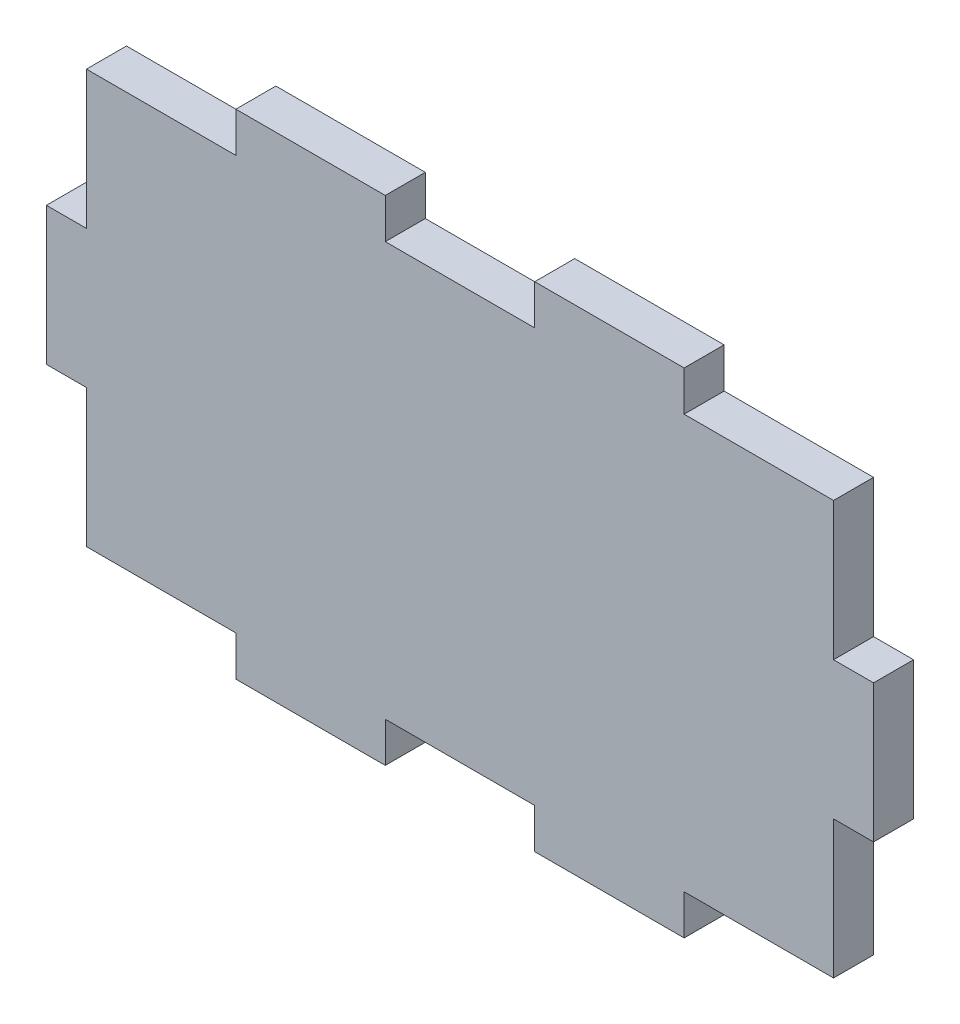
SolidWorks part; units mm, degrees
ref_plane "Plan de face" through (0, 0, 0) normal (0, 0, 1) x (1, 0, 0)
ref_plane "Plan de dessus" through (0, 0, 0) normal (0, 1, 0) x (1, 0, 0)
ref_plane "Plan de droite" through (0, 0, 0) normal (1, 0, 0) x (0, 0, -1)
sketch "Esquisse3" plane through (0, 0, 0) normal (0, 0, 1) x (1, 0, 0)
  line L0 (22.4, 0) -> (33.6, 0)
  line L1 (0, 0) -> (11.2, 0)
  line L2 (0, 0) -> (0, 10.33)
  line L3 (0, 31) -> (11.2, 31)
  line L4 (56, 0) -> (56, 10.33)
  line L6 (11.2, 31) -> (11.2, 34)
  line L8 (11.2, 34) -> (22.4, 34)
  line L9 (11.2, 0) -> (11.2, -3)
  line L10 (11.2, -3) -> (22.4, -3)
  line L11 (22.4, 0) -> (22.4, -3)
  line L13 (33.6, 0) -> (33.6, -3)
  line L14 (33.6, -3) -> (44.8, -3)
  line L15 (44.8, 0) -> (44.8, -3)
  line L16 (22.4, 31) -> (22.4, 34)
  line L18 (33.6, 31) -> (33.6, 34)
  line L19 (33.6, 34) -> (44.8, 34)
  line L20 (44.8, 31) -> (44.8, 34)
  line L21 (56, 20.66) -> (59, 20.66)
  line L23 (0, 20.66) -> (-3, 20.66)
  line L25 (0, 10.33) -> (-3, 10.33)
  line L26 (-3, 20.66) -> (-3, 10.33)
  line L27 (56, 10.33) -> (59, 10.33)
  line L28 (59, 20.66) -> (59, 10.33)
  line L29 (44.8, 0) -> (56, 0)
  line L30 (56, 20.66) -> (56, 31)
  line L31 (44.8, 31) -> (56, 31)
  line L32 (22.4, 31) -> (33.6, 31)
  line L33 (0, 20.66) -> (0, 31)
  dimension "D1" = 56
  dimension "D2" = 31
  dimension "D5" = 11.2
  dimension "D6" = 3
  dimension "D7" = 10.33
  dimension "D9" = 37
  dimension "D10" = 62
  dimension "ep" = 3
extrude "Boss.-Extru.3" add sketch "Esquisse3" along normal blind 3 contours L3 L16 L8 L6 | L23 L26 L25 L2 | L1 L4 L3 L2 | L28 L21 L4 L27 | L15 L1 L13 L14 | L11 L1 L9 L10
equation "\"ep\" = 5mm"
